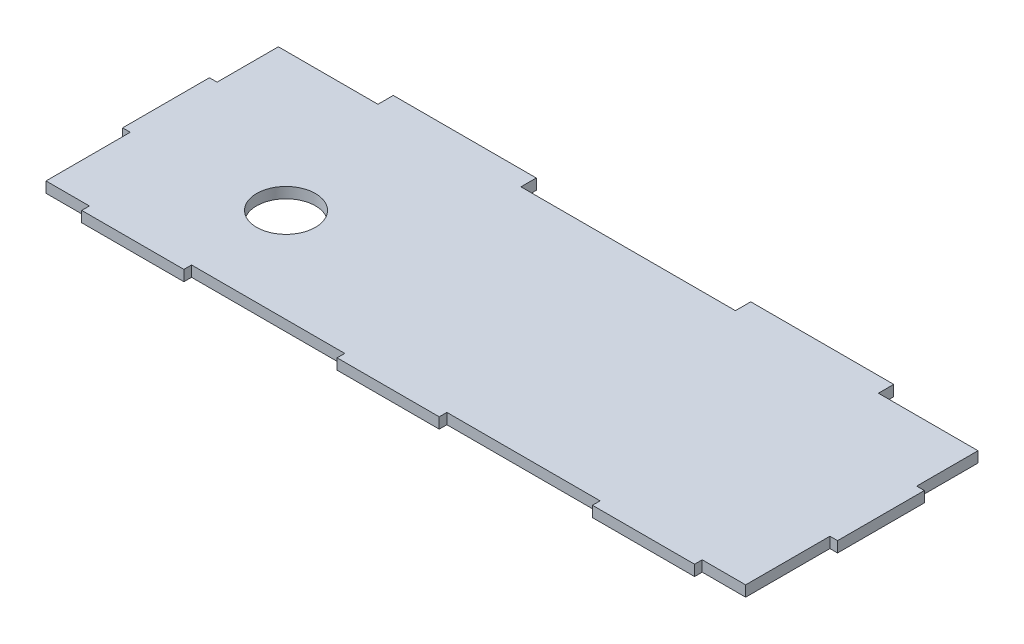
SolidWorks part; units mm, degrees
ref_plane "Front Plane" through (0, 0, 0) normal (0, 0, 1) x (1, 0, 0)
ref_plane "Top Plane" through (0, 0, 0) normal (0, 1, 0) x (1, 0, 0)
ref_plane "Right Plane" through (0, 0, 0) normal (1, 0, 0) x (0, 0, -1)
sketch "Sketch1" plane through (0, 0, 0) normal (0, 1, 0) x (1, 0, 0)
  line L0 (-70, 23.5) -> (-49, 23.5)
  line L1 (-70, -23.5) -> (70, -23.5)
  line L2 (-70, -23.5) -> (-70, 23.5)
  line L4 (70, -23.5) -> (70, 23.5)
  line L5 (-70, -23.5) -> (70, 23.5) construction
  line L6 (-70, 23.5) -> (70, -23.5) construction
  line L7 (-49, 23.5) -> (-49, 26.5)
  line L8 (-49, 26.5) -> (-21, 26.5)
  line L9 (-21, 26.5) -> (-21, 23.5)
  line L10 (-21, 23.5) -> (21, 23.5)
  line L11 (21, 23.5) -> (21, 26.5)
  line L12 (21, 26.5) -> (49, 26.5)
  line L13 (49, 26.5) -> (49, 23.5)
  line L14 (49, 23.5) -> (70, 23.5)
  point P0 (0, 0)
  dimension "D1" = 140
  dimension "D2" = 47
  dimension "D3" = 21
  dimension "D4" = 28
  dimension "D5" = 21
  dimension "D6" = 28
  dimension "D7" = 42
  dimension "D8" = 3
  dimension "D9" = 3
  dimension "D10" = 3
  dimension "D11" = 3
  dimension "D12" = 50
extrude "Boss-Extrude1" add sketch "Sketch1" along normal blind 2.1
sketch "Sketch3" plane through (0, 2.1, 0) normal (0, 1, 0) x (1, 0, 0)
  line L0 (-70, 23.5) -> (-70, -23.5) construction
  line L1 (-70, -23.5) -> (70, -23.5) construction
  circle A0 centre (-40, -3.5) radius 5.75
  dimension "D1" = 30
  dimension "D3" = 11.5
  dimension "D2" = 20
extrude "Cut-Extrude1" cut sketch "Sketch3" against normal through all
sketch "Sketch4" plane through (0, 2.1, 0) normal (0, 1, 0) x (1, 0, 0)
  line L0 (-70, 23.5) -> (-68.5, 23.5)
  line L1 (-49, 23.5) -> (-70, 23.5) construction
  line L2 (-68.5, 23.5) -> (-68.5, 11.5)
  line L3 (-68.5, 11.5) -> (-70, 11.5)
  line L4 (-70, 23.5) -> (-70, -23.5) construction
  line L5 (-70, 11.5) -> (-70, 23.5)
  line L6 (-70, -5.5) -> (-70, -23.5)
  line L7 (-70, -23.5) -> (-60, -23.5)
  line L8 (-70, -23.5) -> (70, -23.5) construction
  line L9 (-60, -23.5) -> (-60, -22)
  line L10 (-60, -22) -> (-68.5, -22)
  line L11 (-68.5, -22) -> (-68.5, -5.5)
  line L12 (-68.5, -5.5) -> (-70, -5.5)
  line L13 (-40, -23.5) -> (-40, -22)
  line L14 (-40, -22) -> (-10, -22)
  line L15 (-10, -22) -> (-10, -23.5)
  line L16 (-10, -23.5) -> (-40, -23.5)
  line L17 (10, -23.5) -> (10, -22)
  line L18 (10, -22) -> (40, -22)
  line L19 (40, -22) -> (40, -23.5)
  line L20 (40, -23.5) -> (10, -23.5)
  line L21 (60, -23.5) -> (70, -23.5)
  line L22 (70, -23.5) -> (70, -5.5)
  line L23 (70, -23.5) -> (70, 23.5) construction
  line L24 (70, -5.5) -> (68.5, -5.5)
  line L25 (68.5, -5.5) -> (68.5, -22)
  line L26 (68.5, -22) -> (60, -22)
  line L27 (60, -22) -> (60, -23.5)
  line L33 (70, 23.5) -> (68.5, 23.5)
  line L34 (68.5, 23.5) -> (68.5, 11.5)
  line L35 (68.5, 11.5) -> (70, 11.5)
  line L36 (70, 11.5) -> (70, 23.5)
  dimension "D1" = 1.5
  dimension "D2" = 12
  dimension "D3" = 18
  dimension "D4" = 1.5
  dimension "D5" = 1.5
  dimension "D6" = 10
  dimension "D7" = 20
  dimension "D8" = 30
  dimension "D9" = 30
  dimension "D10" = 10
  dimension "D11" = 1.5
  dimension "D12" = 1.5
  dimension "D13" = 18
  dimension "D14" = 1.5
  dimension "D15" = 12
  dimension "D16" = 20
  dimension "D17" = 1.5
  dimension "D18" = 1.5
extrude "Cut-Extrude2" cut sketch "Sketch4" against normal through all
